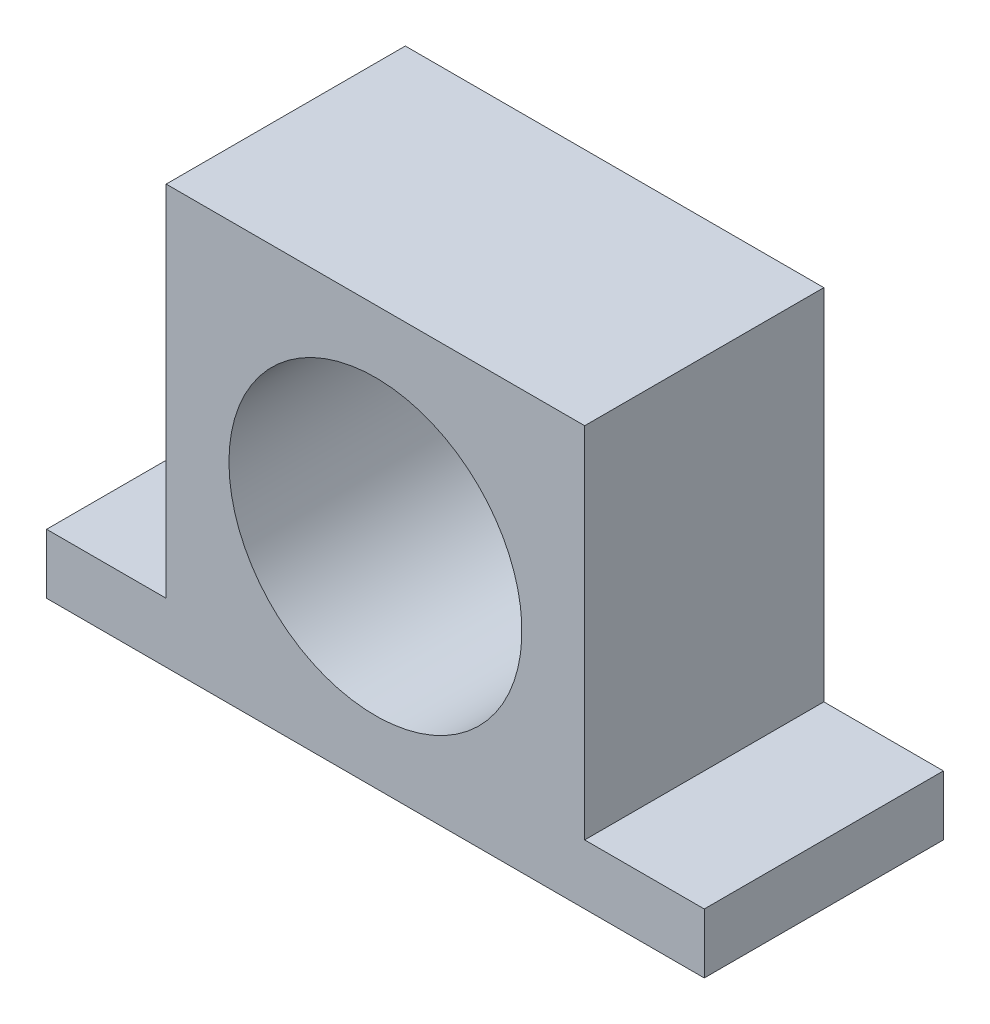
SolidWorks part; units mm, degrees
ref_plane "Front Plane" through (0, 0, 0) normal (0, 0, 1) x (1, 0, 0)
ref_plane "Top Plane" through (0, 0, 0) normal (0, 1, 0) x (1, 0, 0)
ref_plane "Right Plane" through (0, 0, 0) normal (1, 0, 0) x (0, 0, -1)
sketch "Sketch1" plane through (0, 0, 0) normal (0, 0, 1) x (1, 0, 0)
  line L0 (-34.925, -22.225) -> (34.925, -22.225)
  line L1 (-25.4, -22.225) -> (39.6947, -22.225)
  line L2 (-22.225, -15.875) -> (-22.225, 22.225)
  line L3 (-22.225, 22.225) -> (22.225, 22.225)
  line L4 (22.225, -15.875) -> (22.225, 22.225)
  line L7 (-34.925, -22.225) -> (-34.925, -15.875)
  line L8 (34.925, -22.225) -> (34.925, -15.875)
  line L9 (-34.925, -15.875) -> (-22.225, -15.875)
  line L10 (22.225, -15.875) -> (34.925, -15.875)
  circle A0 centre (0, 0) radius 16.8275
  point P0 (0, 0)
  dimension "D1" = 33.655
  dimension "D2" = 44.45
  dimension "D3" = 44.45
  dimension "D4" = 12.7
  dimension "D5" = 12.7
  dimension "D6" = 6.35
  dimension "D7" = 22.225
  dimension "D8" = 22.225
extrude "Boss-Extrude2" add sketch "Sketch1" along normal blind 25.4 contours L3 L4 L10 L8 L0 L7 L9 L2
sketch "Sketch2" plane through (0, 0, 0) normal (0, 0, -1) x (-1, 0, 0)
  circle A0 centre (0, 0) radius 15.5575
  dimension "D1" = 31.115
extrude "Cut-Extrude1" cut sketch "Sketch2" against normal through all
sketch "Sketch3" plane through (0, 22.225, 0) normal (0, 1, 0) x (1, 0, 0)
  line L0 (-34.925, -12.7) -> (41.2689, -12.7) construction
  line L1 (-34.925, -25.4) -> (-34.925, 0) construction
  line L2 (-22.225, 0) -> (22.225, 0) construction
  line L3 (0, -12.7) -> (0, -9.5694) construction
  circle A0 centre (0, -3.81) radius 3.429
  circle A1 centre (0, -21.59) radius 3.429
  dimension "D1" = 6.858
  dimension "D2" = 3.81
extrude "Cut-Extrude2" [suppressed] cut sketch "Sketch3" against normal blind 12.7
